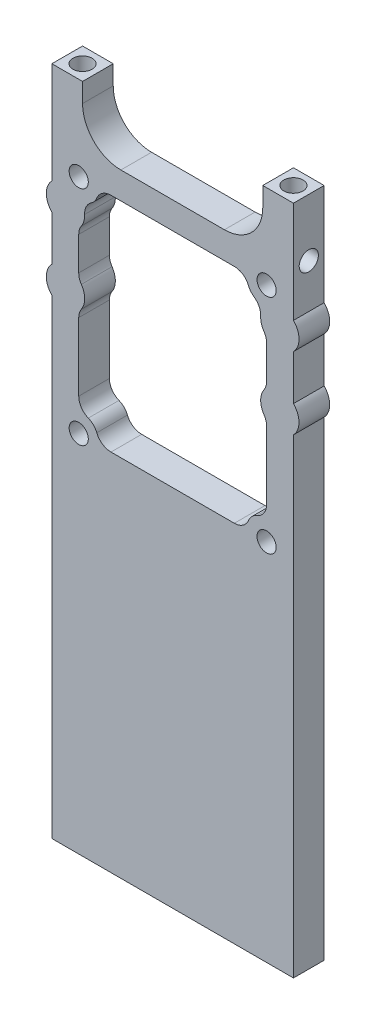
SolidWorks part; units mm, degrees
material "ABS"
ref_plane "Спереди" through (0, 0, 0) normal (0, 0, 1) x (1, 0, 0)
ref_plane "Сверху" through (0, 0, 0) normal (0, 1, 0) x (1, 0, 0)
ref_plane "Справа" through (0, 0, 0) normal (1, 0, 0) x (0, 0, -1)
sketch "Эскиз1" plane through (0, 0, 0) normal (0, 0, 1) x (1, 0, 0)
  line L0 (-23.5, 87.5) -> (-23.5, 72.5)
  line L1 (-31.5, -87.5) -> (31.5, -87.5)
  line L2 (-31.5, -87.5) -> (-31.5, 87.5)
  line L3 (-31.5, 87.5) -> (31.5, 87.5)
  line L4 (31.5, -87.5) -> (31.5, 87.5)
  line L5 (-31.5, -87.5) -> (31.5, 87.5) construction
  line L6 (-31.5, 87.5) -> (31.5, -87.5) construction
  line L7 (-23.5, 72.5) -> (23.5, 72.5)
  line L8 (23.5, 72.5) -> (23.5, 87.5)
  line L9 (-27.5, 87.5) -> (-27.5, 27.2149) construction
  line L10 (0, 87.5) -> (0, 0) construction
  line L11 (27.5, 87.5) -> (27.5, 27.2149) construction
  point P0 (0, 0)
  dimension "D1" = 8
  dimension "D2" = 8
  dimension "D3" = 4
  dimension "D4" = 55
  dimension "D5" = 15
  dimension "D6" = 175
extrude "Бобышка-Вытянуть1" add sketch "Эскиз1" along normal blind 8 contours L8 L7 L0 L3 L2 L1 L4
sketch "Эскиз2" plane through (0, 87.5, 0) normal (0, 1, 0) x (1, 0, 0)
  line L0 (-23.5, 0) -> (-31.5, -8) construction
  line L1 (0, 0) -> (0, -8) construction
  line L2 (-23.5, -8) -> (23.5, -8) construction
  circle A0 centre (-27.5, -4) radius 2.5
  circle A1 centre (27.5, -4) radius 2.5
  dimension "D1" = 5
extrude "Вырез-Вытянуть1" cut sketch "Эскиз2" against normal blind 6
sketch "Эскиз3" plane through (0, 0, 8) normal (0, 0, 1) x (1, 0, 0)
  line L0 (0, 72.5) -> (0, -87.5) construction
  line L1 (-23.5, 72.5) -> (23.5, 72.5) construction
  line L2 (-31.5, -87.5) -> (31.5, -87.5) construction
  line L4 (-24.5, 7.5) -> (24.5, 7.5) construction
  line L5 (-24.5, 7.5) -> (-24.5, 65.5) construction
  line L6 (-24.5, 65.5) -> (24.5, 65.5) construction
  line L7 (24.5, 7.5) -> (24.5, 65.5) construction
  line L8 (-24.5, 7.5) -> (24.5, 65.5) construction
  line L9 (-24.5, 65.5) -> (24.5, 7.5) construction
  circle A0 centre (-24.5, 65.5) radius 2.5
  circle A1 centre (24.5, 65.5) radius 2.5
  circle A2 centre (24.5, 7.5) radius 2.5
  circle A3 centre (-24.5, 7.5) radius 2.5
  point P6 (0, 0)
  point P16 (0, 36.5)
  point P17 (28.0947, -15.8548)
  point P18 (0, 0)
  point P19 (-24.5, -15.2034)
  dimension "D3" = 5
  dimension "D1" = 49
  dimension "D2" = 7
  dimension "D4" = 58
extrude "Вырез-Вытянуть2" cut sketch "Эскиз3" against normal blind 6
fillet "Скругление1" radius 10 2 edges at (23.5, 72.5, 4) (-23.5, 72.5, 4)
sketch "Эскиз4" plane through (0, 0, 8) normal (0, 0, 1) x (1, 0, 0)
  line L0 (24.5, 65.5) -> (-24.5, 7.5) construction
  line L1 (31.5, -87.5) -> (31.5, 87.5) construction
  line L2 (-24.5, 60.5) -> (24.5, 60.5)
  line L3 (-24.5, 60.5) -> (-24.5, 12.5)
  line L4 (-24.5, 12.5) -> (24.5, 12.5)
  line L5 (24.5, 60.5) -> (24.5, 12.5)
  line L6 (-24.5, 60.5) -> (24.5, 12.5) construction
  line L7 (-24.5, 12.5) -> (24.5, 60.5) construction
  line L8 (-13.5, 72.5) -> (13.5, 72.5) construction
  line L9 (-19.5, 7.5) -> (19.5, 7.5)
  line L10 (-19.5, 7.5) -> (-19.5, 65.5)
  line L11 (-19.5, 65.5) -> (19.5, 65.5)
  line L12 (19.5, 7.5) -> (19.5, 65.5)
  line L13 (-19.5, 7.5) -> (19.5, 65.5) construction
  line L14 (-19.5, 65.5) -> (19.5, 7.5) construction
  point P4 (0, 36.5)
  point P11 (0, 36.5)
  dimension "D1" = 7
  dimension "D2" = 5
  dimension "D3" = 5
  dimension "D4" = 7
extrude "Вырез-Вытянуть3" cut sketch "Эскиз4" against normal blind 21 contours L4 L12 L2 L10 | L4 L10 L2 L3 | L2 L12 L11 L10 | L12 L4 L5 L2 | L9 L12 L4 L10
sketch "Эскиз5" plane through (0, 0, 0) normal (0, 0, -1) x (-1, 0, 0)
  line L0 (0, 72.5) -> (0, -87.5) construction
  line L1 (13.5, 72.5) -> (-13.5, 72.5) construction
  line L2 (31.5, -87.5) -> (-31.5, -87.5) construction
  line L4 (-27.95, 57.5) -> (27.95, 57.5) construction
  line L5 (-27.95, 57.5) -> (-27.95, 38.7) construction
  line L6 (-27.95, 38.7) -> (27.95, 38.7) construction
  line L7 (27.95, 57.5) -> (27.95, 38.7) construction
  line L8 (-27.95, 57.5) -> (27.95, 38.7) construction
  line L9 (-27.95, 38.7) -> (27.95, 57.5) construction
  circle A0 centre (-27.95, 57.5) radius 5
  circle A1 centre (-27.95, 38.7) radius 5
  circle A2 centre (27.95, 38.7) radius 5
  circle A3 centre (27.95, 57.5) radius 5
  point P6 (0, 48.1)
  dimension "D4" = 10
  dimension "D1" = 18.8
  dimension "D2" = 55.9
  dimension "D3" = 15
extrude "Бобышка-Вытянуть2" add sketch "Эскиз5" against normal up to surface (8 mm away) up to face at (0, 36.5, 8)
fillet "Скругление2" radius 4 4 edges at (-19.5, 12.5, 4) (19.5, 12.5, 4) (19.5, 60.5, 4) (-19.5, 60.5, 4)
fillet "Скругление3" radius 4 14 edges at (-24.5, 42.319, 4) (-24.5, 35.081, 4) (-24.5, 53.881, 4) (-23.95, 60.5, 4) (-19.5, 65.5, 4) (24.5, 42.319, 4) (24.5, 35.081, 4) (24.5, 53.881, 4) (19.5, 65.5, 4) (23.95, 60.5, 4) (24.5, 12.5, 4) (19.5, 7.5, 4) (-19.5, 7.5, 4) (-24.5, 12.5, 4)
sketch "Эскиз6" plane through (0, 0, 0) normal (0, 0, -1) x (-1, 0, 0)
  circle A0 centre (-27.95, 57.5) radius 2.5
  circle A1 centre (27.95, 57.5) radius 2.5
  circle A2 centre (27.95, 38.7) radius 2.5
  circle A3 centre (-27.95, 38.7) radius 2.5
  dimension "D1" = 5
extrude "Вырез-Вытянуть4" cut sketch "Эскиз6" against normal blind 6
sketch "Эскиз7" plane through (-31.5, 0, 0) normal (-1, 0, 0) x (0, 0, 1)
  line L0 (4, 87.5) -> (4, 51.4454) construction
  line L1 (4, 81.5) -> (4, 87.5) construction
  line L3 (8, 87.5) -> (0, 87.5) construction
  circle A0 centre (4, 72.5) radius 2.5
  point P6 (4, 51.4454)
  point P7 (0, 0)
  dimension "D1" = 5
  dimension "D2" = 15
extrude "Вырез-Вытянуть5" cut sketch "Эскиз7" against normal blind 6
mirror "Зеркальное отражение1" about plane through (0, 0, 0) normal (1, 0, 0) of "Вырез-Вытянуть5"
